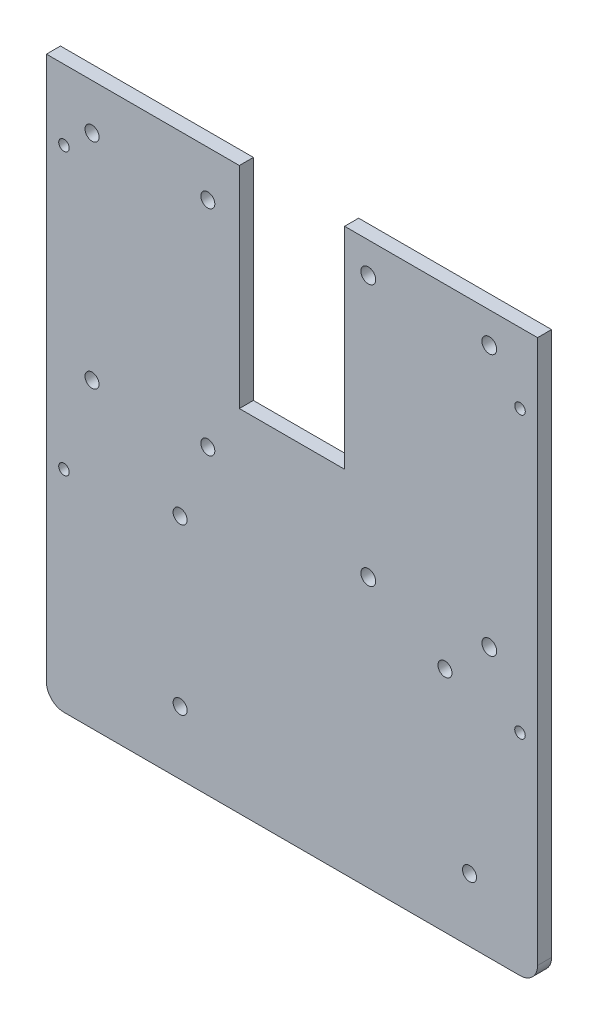
SolidWorks part; units mm, degrees
ref_plane "前视基准面" through (0, 0, 0) normal (0, 0, 1) x (1, 0, 0)
ref_plane "上视基准面" through (0, 0, 0) normal (0, 1, 0) x (1, 0, 0)
ref_plane "右视基准面" through (0, 0, 0) normal (1, 0, 0) x (0, 0, -1)
sketch "草图1" plane through (0, 0, 0) normal (0, 0, 1) x (1, 0, 0)
  line L0 (-38.6497, 0) -> (37.2518, 0) construction
  line L1 (-70, 100) -> (70, 100)
  line L2 (-70, 100) -> (-70, -100)
  line L3 (-70, -100) -> (70, -100)
  line L4 (70, 100) -> (70, -100)
  line L5 (-70, 100) -> (70, -100) construction
  line L6 (-70, -100) -> (70, 100) construction
  line L7 (0, 33.0222) -> (0, -43.9262) construction
  circle A0 centre (-65, 40) radius 1.5
  circle A1 centre (-65, -40) radius 1.5
  circle A2 centre (65, -40) radius 1.5
  circle A3 centre (65, 40) radius 1.5
  point P0 (0, 0)
  dimension "D3" = 5
  dimension "D4" = 3
  dimension "D1" = 140
  dimension "D2" = 200
  dimension "D5" = 40
extrude "凸台-拉伸1" add sketch "草图1" along normal blind 4
sketch "草图2" plane through (0, 0, 4) normal (0, 0, 1) x (1, 0, 0)
  line L0 (70, -100) -> (70, 100) construction
  line L1 (70, 100) -> (90, 100)
  line L2 (70, 100) -> (70, 80)
  line L3 (70, 80) -> (90, 80)
  line L4 (90, 100) -> (90, 80)
  dimension "D1" = 20
  dimension "D2" = 20
extrude "凸台-拉伸2" add sketch "草图2" against normal blind 4
fillet "圆角1" radius 3 2 edges at (90, 100, 2) (90, 80, 2)
mirror "镜向1" about plane through (0, 0, 0) normal (1, 0, 0) of "凸台-拉伸2", "圆角1"
sketch "草图3" plane through (0, 0, 4) normal (0, 0, 1) x (1, 0, 0)
  line L0 (87, 100) -> (-87, 100) construction
  line L1 (-70, 100) -> (-62, 100)
  line L2 (-70, 100) -> (-70, 130)
  line L3 (-70, 130) -> (-62, 130)
  line L4 (-62, 100) -> (-62, 130)
  circle A0 centre (-66, 126) radius 1.75
  dimension "D3" = 3.5
  dimension "D1" = 8
  dimension "D2" = 30
  dimension "D4" = 4
extrude "凸台-拉伸3" add sketch "草图3" against normal blind 4
fillet "圆角2" radius 3 2 edges at (-70, 100, 2) (-62, 100, 2)
mirror "镜向2" about plane through (0, 0, 0) normal (1, 0, 0) of "凸台-拉伸3", "圆角2"
fillet "圆角3" radius 5 2 edges at (-70, -100, 2) (70, -100, 2)
sketch "草图4" plane through (0, 0, 0) normal (0, 0, -1) x (-1, 0, 0)
  line L1 (-59, 100) -> (59, 100) construction
  line L2 (0, 120) -> (0, 43.57) construction
  line L3 (-33.7864, 100) -> (33.7864, 100)
  arc A0 (-16.5072, 108.7078) -> (16.5072, 108.7078) centre (0, 120) ccw
  arc A1 (46.5063, 131.5664) -> (16.5072, 108.7078) centre (66.0287, 74.8313) ccw
  arc A2 (48.2539, 128.0028) -> (46.5063, 131.5664) centre (47.157, 129.6752) ccw
  arc A3 (-48.2539, 128.0028) -> (-46.5063, 131.5664) centre (-47.157, 129.6752) cw
  arc A4 (-46.5063, 131.5664) -> (-16.5072, 108.7078) centre (-66.0287, 74.8313) cw
  spline S0 degree 3 poles (33.7864, 100) (33.3848, 111.2431) (38.9442, 121.8971) (48.2539, 128.0028) knots 0 0 0 0 0.661941 0.661941 0.661941 0.661941
  spline S1 degree 3 poles (-33.7864, 100) (-33.3848, 111.2431) (-38.9442, 121.8971) (-48.2539, 128.0028) knots 0 0 0 0 0.661941 0.661941 0.661941 0.661941
  line M16 (59, 100) -> (-59, 100)
  dimension "D1" = 40
  dimension "D2" = 120
  dimension "D3" = 2
extrude "凸台-拉伸4" add sketch "草图4" against normal blind 4 contours S1 L3 A0 A4 A3 | S0 A2 A1 A0 M16
sketch "草图5" plane through (0, 0, 0) normal (0, 0, -1) x (-1, 0, 0)
  line L0 (-70, 60) -> (70, 60)
  line L17 (-65, -100) -> (65, -100)
  line L18 (70, -95) -> (70, 80)
  line L19 (70, 80) -> (87, 80)
  line L20 (90, 83) -> (90, 97)
  line L21 (87, 100) -> (73, 100)
  line L22 (70, 103) -> (70, 130)
  line L23 (70, 130) -> (62, 130)
  line L24 (62, 130) -> (62, 103)
  line L25 (59, 100) -> (33.7864, 100)
  line L26 (-33.7864, 100) -> (-59, 100)
  line L27 (-62, 103) -> (-62, 130)
  line L28 (-62, 130) -> (-70, 130)
  line L29 (-70, 130) -> (-70, 103)
  line L30 (-73, 100) -> (-87, 100)
  line L31 (-90, 97) -> (-90, 83)
  line L32 (-87, 80) -> (-70, 80)
  line L33 (-70, 80) -> (-70, -95)
  line L34 (-65, -100) -> (65, -100)
  line L35 (70, -95) -> (70, 80)
  line L36 (70, 80) -> (87, 80)
  line L37 (90, 83) -> (90, 97)
  line L38 (87, 100) -> (73, 100)
  line L39 (70, 103) -> (70, 130)
  line L40 (70, 130) -> (62, 130)
  line L41 (62, 130) -> (62, 103)
  line L42 (59, 100) -> (33.7864, 100)
  line L43 (-33.7864, 100) -> (-59, 100)
  line L44 (-62, 103) -> (-62, 130)
  line L45 (-62, 130) -> (-70, 130)
  line L46 (-70, 130) -> (-70, 103)
  line L47 (-73, 100) -> (-87, 100)
  line L48 (-90, 97) -> (-90, 83)
  line L49 (-87, 80) -> (-70, 80)
  line L50 (-70, 80) -> (-70, -95)
  arc A15 (65, -100) -> (70, -95) centre (65, -95) ccw
  arc A16 (87, 80) -> (90, 83) centre (87, 83) ccw
  arc A17 (90, 97) -> (87, 100) centre (87, 97) ccw
  arc A18 (70, 103) -> (73, 100) centre (73, 103) ccw
  arc A19 (59, 100) -> (62, 103) centre (59, 103) ccw
  arc A20 (48.2539, 128.0028) -> (46.5063, 131.5664) centre (47.157, 129.6752) ccw
  arc A21 (46.5063, 131.5664) -> (16.5072, 108.7078) centre (66.0287, 74.8313) ccw
  arc A22 (-16.5072, 108.7078) -> (16.5072, 108.7078) centre (0, 120) ccw
  arc A23 (-16.5072, 108.7078) -> (-46.5063, 131.5664) centre (-66.0287, 74.8313) ccw
  arc A24 (-46.5063, 131.5664) -> (-48.2539, 128.0028) centre (-47.157, 129.6752) ccw
  arc A25 (-62, 103) -> (-59, 100) centre (-59, 103) ccw
  arc A26 (-73, 100) -> (-70, 103) centre (-73, 103) ccw
  arc A27 (-87, 100) -> (-90, 97) centre (-87, 97) ccw
  arc A28 (-90, 83) -> (-87, 80) centre (-87, 83) ccw
  arc A29 (-70, -95) -> (-65, -100) centre (-65, -95) ccw
  arc A30 (65, -100) -> (70, -95) centre (65, -95) ccw
  arc A31 (87, 80) -> (90, 83) centre (87, 83) ccw
  arc A32 (90, 97) -> (87, 100) centre (87, 97) ccw
  arc A33 (70, 103) -> (73, 100) centre (73, 103) ccw
  arc A34 (59, 100) -> (62, 103) centre (59, 103) ccw
  arc A35 (48.2539, 128.0028) -> (46.5063, 131.5664) centre (47.157, 129.6752) ccw
  arc A36 (46.5063, 131.5664) -> (16.5072, 108.7078) centre (66.0287, 74.8313) ccw
  arc A37 (-16.5072, 108.7078) -> (16.5072, 108.7078) centre (0, 120) ccw
  arc A38 (-16.5072, 108.7078) -> (-46.5063, 131.5664) centre (-66.0287, 74.8313) ccw
  arc A39 (-46.5063, 131.5664) -> (-48.2539, 128.0028) centre (-47.157, 129.6752) ccw
  arc A40 (-62, 103) -> (-59, 100) centre (-59, 103) ccw
  arc A41 (-73, 100) -> (-70, 103) centre (-73, 103) ccw
  arc A42 (-87, 100) -> (-90, 97) centre (-87, 97) ccw
  arc A43 (-90, 83) -> (-87, 80) centre (-87, 83) ccw
  arc A44 (-70, -95) -> (-65, -100) centre (-65, -95) ccw
  spline S2 degree 3 poles (3130.1002, 2565.919) (-2380.5286, -3185.8947) (1580.4228, 3909.0008) (-427.2839, -3801.3391) knots -5.976918 -5.976918 -5.976918 -5.976918 6.676098 6.676098 6.676098 6.676098 only from (33.7864, 100) to (48.2539, 128.0028)
  spline S3 degree 3 poles (427.3119, -3801.4466) (-1580.4624, 3909.0776) (2380.5653, -3185.9413) (-3130.1233, 2565.9432) knots -6.014216 -6.014216 -6.014216 -6.014216 6.638877 6.638877 6.638877 6.638877 only from (-48.2539, 128.0028) to (-33.7864, 100)
  spline S4 degree 3 poles (33.7864, 100) (33.3848, 111.2431) (38.9442, 121.8971) (48.2539, 128.0028) knots 0 0 0 0 0.661941 0.661941 0.661941 0.661941
  spline S5 degree 3 poles (-48.2539, 128.0028) (-38.9442, 121.8971) (-33.3848, 111.2431) (-33.7864, 100) knots 0 0 0 0 0.661941 0.661941 0.661941 0.661941
  line M38 (70, -95) -> (70, 80)
  line M39 (70, 80) -> (87, 80)
  arc M40 (87, 80) -> (90, 83) centre (87, 83) ccw
  line M41 (90, 83) -> (90, 97)
  arc M42 (90, 97) -> (87, 100) centre (87, 97) ccw
  line M43 (87, 100) -> (73, 100)
  arc M44 (73, 100) -> (70, 103) centre (73, 103) cw
  line M45 (70, 103) -> (70, 130)
  line M46 (70, 130) -> (62, 130)
  line M47 (62, 130) -> (62, 103)
  arc M48 (62, 103) -> (59, 100) centre (59, 103) cw
  line M49 (59, 100) -> (33.7864, 100)
  spline M50 degree 3 poles (33.7864, 100) (33.3848, 111.2431) (38.9442, 121.8971) (48.2539, 128.0028) knots 0 0 0 0 0.661941 0.661941 0.661941 0.661941
  arc M51 (48.2539, 128.0028) -> (46.5063, 131.5664) centre (47.157, 129.6752) ccw
  arc M52 (46.5063, 131.5664) -> (16.5072, 108.7078) centre (66.0287, 74.8313) ccw
  arc M53 (16.5072, 108.7078) -> (-16.5072, 108.7078) centre (0, 120) cw
  arc M54 (-16.5072, 108.7078) -> (-46.5063, 131.5664) centre (-66.0287, 74.8313) ccw
  arc M55 (-46.5063, 131.5664) -> (-48.2539, 128.0028) centre (-47.157, 129.6752) ccw
  spline M56 degree 3 poles (-48.2539, 128.0028) (-38.9442, 121.8971) (-33.3848, 111.2431) (-33.7864, 100) knots 0 0 0 0 0.661941 0.661941 0.661941 0.661941
  line M57 (-33.7864, 100) -> (-59, 100)
  arc M58 (-59, 100) -> (-62, 103) centre (-59, 103) cw
  line M59 (-62, 103) -> (-62, 130)
  line M60 (-62, 130) -> (-70, 130)
  line M61 (-70, 130) -> (-70, 103)
  arc M62 (-70, 103) -> (-73, 100) centre (-73, 103) cw
  line M63 (-73, 100) -> (-87, 100)
  arc M64 (-87, 100) -> (-90, 97) centre (-87, 97) ccw
  line M65 (-90, 97) -> (-90, 83)
  arc M66 (-90, 83) -> (-87, 80) centre (-87, 83) ccw
  line M67 (-87, 80) -> (-70, 80)
  line M68 (-70, 80) -> (-70, -95)
  circle M74 centre (66, 126) radius 1.75
  circle M75 centre (-66, 126) radius 1.75
  dimension "D2" = 20
  dimension "D1" = 0
extrude "切除-拉伸1" cut sketch "草图5" against normal blind 10 contours L0 M68 M38 M39 M40 M41 M42 M43 M44 M45 M46 M47 M48 M49 M50 M51 M52 M53 M54 M55 M56 M57 M58 M59 M60 M61 M62 M63 M64 M65 M66 M67 M75 M74
sketch "草图6" plane through (0, 0, 0) normal (0, 0, -1) x (-1, 0, 0)
  line L0 (-70, 60) -> (70, 60) construction
  line L1 (-15, 60) -> (15, 60)
  line L2 (-15, 60) -> (-15, 0)
  line L3 (-15, 0) -> (15, 0)
  line L4 (0, 60) -> (0, 0) construction
  line L5 (15, 60) -> (15, 0)
  dimension "D1" = 15
  dimension "D2" = 0
extrude "切除-拉伸2" cut sketch "草图6" against normal blind 10
sketch "草图7" plane through (0, 0, 4) normal (0, 0, 1) x (1, 0, 0)
  circle A0 centre (-57, -14) radius 2 construction
  circle A1 centre (-24, -14) radius 2 construction
  circle A2 centre (-57, 47) radius 2 construction
  circle A3 centre (-24, 47) radius 2 construction
  circle A4 centre (-31.89, -82) radius 2 construction
  circle A5 centre (-31.89, -35) radius 2 construction
  circle A6 centre (50.61, -82) radius 2 construction
  circle A7 centre (43.61, -35) radius 2 construction
  circle A8 centre (21.75, -23.25) radius 2.1123 construction
  circle A9 centre (21.75, 51.25) radius 2.1123 construction
  circle A10 centre (56.25, -23.25) radius 2.1123 construction
  circle A11 centre (56.25, 51.25) radius 2.1123 construction
  circle A48 centre (56.25, 51.25) radius 2.1123
  circle A49 centre (56.25, -23.25) radius 2.1123
  circle A50 centre (21.75, 51.25) radius 2.1123
  circle A51 centre (21.75, -23.25) radius 2.1123
  circle A52 centre (43.61, -35) radius 2
  circle A53 centre (50.61, -82) radius 2
  circle A54 centre (-31.89, -35) radius 2
  circle A55 centre (-31.89, -82) radius 2
  circle A56 centre (-24, 47) radius 2
  circle A57 centre (-57, 47) radius 2
  circle A58 centre (-24, -14) radius 2
  circle A59 centre (-57, -14) radius 2
extrude "切除-拉伸3" cut sketch "草图7" against normal blind 10
